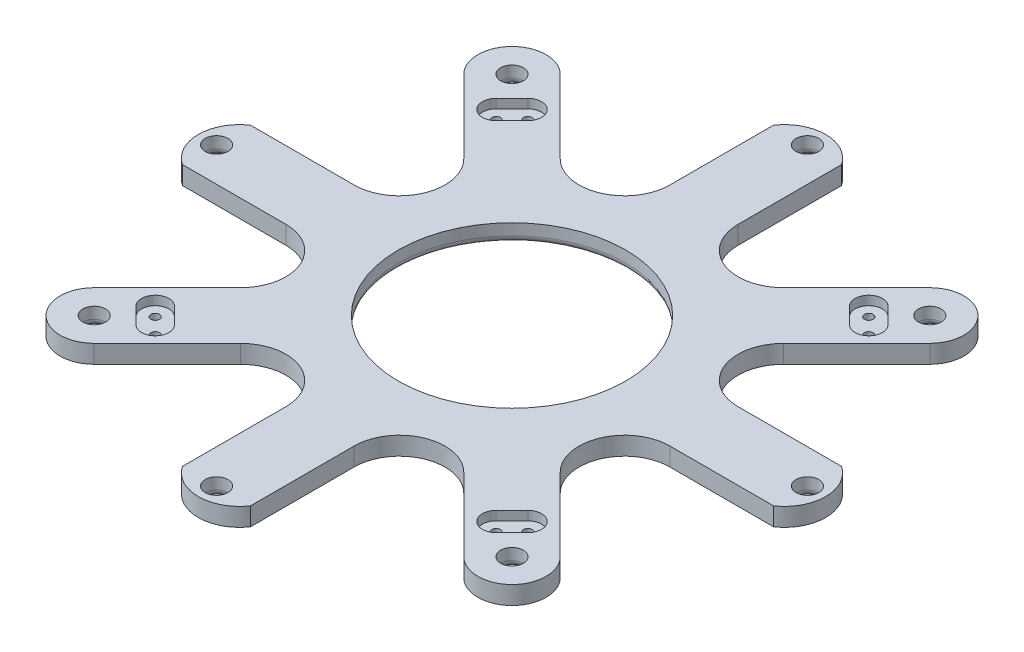
SolidWorks part; units mm, degrees
ref_plane "Спереди" through (0, 0, 0) normal (0, 0, 1) x (1, 0, 0)
ref_plane "Сверху" through (0, 0, 0) normal (0, 1, 0) x (1, 0, 0)
ref_plane "Справа" through (0, 0, 0) normal (1, 0, 0) x (0, 0, -1)
sketch "Эскиз1" plane through (0, 0, 0) normal (0, 1, 0) x (1, 0, 0)
  line L0 (-130, 15) -> (130, 15)
  line L4 (0, 65.7238) -> (0, 0) construction
  line L5 (0, 0) -> (156.4205, 0) construction
  line L6 (-130, -15) -> (130, -15)
  circle A3 centre (130, 0) radius 5
  arc A4 (130, 15) -> (130, -15) centre (120, 0) cw
  circle A6 centre (-130, 0) radius 5
  arc A7 (-130, 15) -> (-130, -15) centre (-120, 0) ccw
  point P6 (0, 0)
  point P7 (0, 0)
  dimension "D2" = 10
  dimension "D1" = 260
  dimension "D3" = 120
  dimension "D4" = 30
extrude "Бобышка-Вытянуть1" add sketch "Эскиз1" along normal blind 8
sketch "Эскиз2" plane through (0, 0, 0) normal (0, 1, 0) x (1, 0, 0)
  line L0 (-15, 130) -> (-15, -130)
  line L4 (-167.7576, 0) -> (0, 0) construction
  line L5 (0, 0) -> (0, 171.0199) construction
  line L6 (15, 130) -> (15, -130)
  circle A2 centre (0, 130) radius 5
  arc A4 (-15, 130) -> (15, 130) centre (0, 120) cw
  arc A6 (-15, -130) -> (15, -130) centre (0, -120) ccw
  circle A7 centre (0, -130) radius 5
  point P4 (0, 0)
  dimension "D2" = 10
  dimension "D1" = 120
  dimension "D3" = 130
  dimension "D4" = 30
extrude "Бобышка-Вытянуть2" add sketch "Эскиз2" along normal blind 8
sketch "Эскиз3" plane through (0, 0, 0) normal (0, 1, 0) x (1, 0, 0)
  line L0 (0, 177.7939) -> (0, 0) construction
  line L1 (0, 0) -> (202.5323, 0) construction
  line L2 (0, 0) -> (135.2393, 135.2393) construction
  line L3 (91.9239, 91.9239) -> (-91.9239, -91.9239) construction
  line L4 (102.5305, 81.3173) -> (-81.3173, -102.5305)
  line L5 (81.3173, 102.5305) -> (-102.5305, -81.3173)
  arc A0 (102.5305, 81.3173) -> (81.3173, 102.5305) centre (91.9239, 91.9239) ccw
  arc A1 (-102.5305, -81.3173) -> (-81.3173, -102.5305) centre (-91.9239, -91.9239) ccw
  circle A2 centre (91.9239, 91.9239) radius 5
  circle A3 centre (-91.9239, -91.9239) radius 5
  point P7 (0, 0)
  dimension "D4" = 10
  dimension "D1" = 45
  dimension "D2" = 260
  dimension "D3" = 30
extrude "Бобышка-Вытянуть3" add sketch "Эскиз3" along normal blind 8
sketch "Эскиз4" plane through (0, 0, 0) normal (0, 1, 0) x (1, 0, 0)
  line L0 (0, 119.1481) -> (0, 0) construction
  line L1 (0, 0) -> (-130.6682, 130.6682) construction
  line L2 (-91.9239, 91.9239) -> (91.9239, -91.9239) construction
  line L3 (-81.3173, 102.5305) -> (102.5305, -81.3173)
  line L4 (-102.5305, 81.3173) -> (81.3173, -102.5305)
  arc A0 (-81.3173, 102.5305) -> (-102.5305, 81.3173) centre (-91.9239, 91.9239) ccw
  arc A1 (81.3173, -102.5305) -> (102.5305, -81.3173) centre (91.9239, -91.9239) ccw
  circle A2 centre (-91.9239, 91.9239) radius 5
  circle A3 centre (91.9239, -91.9239) radius 5
  point P6 (0, 0)
  dimension "D3" = 10
  dimension "D1" = 260
  dimension "D2" = 30
extrude "Бобышка-Вытянуть4" add sketch "Эскиз4" along normal blind 8
fillet "Скругление2" radius 20 8 edges at (-15, 4, 36.2132) (15, 4, 36.2132) (15, 4, -36.2132) (-15, 4, -36.2132) (-36.2132, 4, 15) (-36.2132, 4, -15) (36.2132, 4, 15) (36.2132, 4, -15)
sketch "Эскиз5" plane through (0, 0, 0) normal (0, 1, 0) x (1, 0, 0)
  line L0 (-82, -75) -> (82, -75) construction
  line L1 (-75, -82) -> (75, -82) construction
  line L2 (-75, -82) -> (-75, 82) construction
  line L3 (-75, 82) -> (75, 82) construction
  line L4 (75, -82) -> (75, 82) construction
  line L5 (0, 82) -> (0, -82) construction
  line L6 (-75, 0) -> (75, 0) construction
  line L7 (-82, -75) -> (82, -75) construction
  line L8 (-82, -75) -> (-82, 75) construction
  line L9 (-82, 75) -> (82, 75) construction
  line L10 (82, -75) -> (82, 75) construction
  line L11 (0, 75) -> (0, -75) construction
  line L12 (-82, 0) -> (82, 0) construction
  line L13 (-75, -82) -> (75, -82) construction
  circle A0 centre (75, 82) radius 1.9
  circle A1 centre (82, 75) radius 1.9
  circle A2 centre (-82, 75) radius 1.9
  circle A3 centre (-75, 82) radius 1.9
  circle A4 centre (-75, -82) radius 1.9
  circle A5 centre (-82, -75) radius 1.9
  circle A6 centre (82, -75) radius 1.9
  circle A7 centre (75, -82) radius 1.9
  circle A8 centre (0, 0) radius 50
  point P0 (0, 0)
  point P4 (0, 0)
  dimension "D5" = 3.8
  dimension "D6" = 100
  dimension "D1" = 150
  dimension "D2" = 164
  dimension "D3" = 164
  dimension "D4" = 150
extrude "Вырез-Вытянуть1" cut sketch "Эскиз5" along normal blind 10
sketch "Эскиз6" plane through (0, 8, 0) normal (0, 1, 0) x (1, 0, 0)
  line L0 (-82, 75) -> (-75, 82) construction
  line L1 (-86.2426, 79.2426) -> (-79.2426, 86.2426)
  line L2 (-77.7574, 70.7574) -> (-70.7574, 77.7574)
  line L3 (75, 82) -> (82, 75) construction
  line L4 (79.2426, 86.2426) -> (86.2426, 79.2426)
  line L5 (70.7574, 77.7574) -> (77.7574, 70.7574)
  line L6 (75, -82) -> (82, -75) construction
  line L7 (70.7574, -77.7574) -> (77.7574, -70.7574)
  line L8 (79.2426, -86.2426) -> (86.2426, -79.2426)
  line L9 (-82, -75) -> (-75, -82) construction
  line L10 (-77.7574, -70.7574) -> (-70.7574, -77.7574)
  line L11 (-86.2426, -79.2426) -> (-79.2426, -86.2426)
  arc A0 (-86.2426, 79.2426) -> (-77.7574, 70.7574) centre (-82, 75) ccw
  arc A1 (-70.7574, 77.7574) -> (-79.2426, 86.2426) centre (-75, 82) ccw
  arc A2 (79.2426, 86.2426) -> (70.7574, 77.7574) centre (75, 82) ccw
  arc A3 (77.7574, 70.7574) -> (86.2426, 79.2426) centre (82, 75) ccw
  arc A4 (70.7574, -77.7574) -> (79.2426, -86.2426) centre (75, -82) ccw
  arc A5 (86.2426, -79.2426) -> (77.7574, -70.7574) centre (82, -75) ccw
  arc A6 (-77.7574, -70.7574) -> (-86.2426, -79.2426) centre (-82, -75) ccw
  arc A7 (-79.2426, -86.2426) -> (-70.7574, -77.7574) centre (-75, -82) ccw
  point P4 (-78.5, 78.5)
  point P13 (78.5, 78.5)
  point P22 (78.5, -78.5)
  point P31 (-78.5, -78.5)
  dimension "D1" = 12
  dimension "D2" = 12
  dimension "D3" = 12
  dimension "D4" = 12
extrude "Вырез-Вытянуть2" cut sketch "Эскиз6" against normal blind 4
fillet "Скругление3" radius 3 9 edges at (91.9239, 0, 96.9239) (0, 0, 125) (-91.9239, 0, 96.9239) (-91.9239, 0, -86.9239) (-130, 0, -5) (0, 0, -125) (91.9239, 0, -86.9239) (130, 0, 5) (0, 0, 50)
